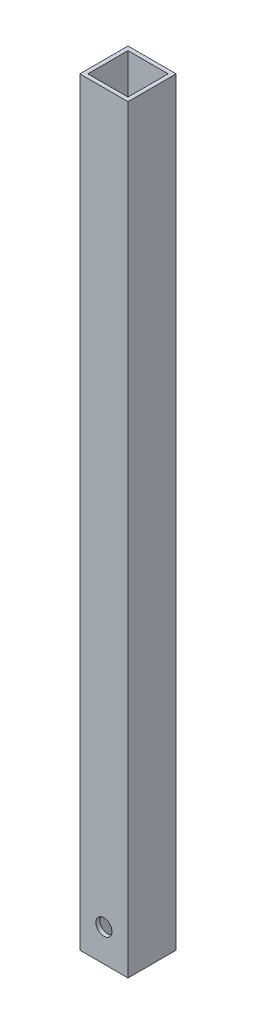
SolidWorks part; units mm, degrees
ref_plane "Front Plane" through (0, 0, 0) normal (0, 0, 1) x (1, 0, 0)
ref_plane "Top Plane" through (0, 0, 0) normal (0, 1, 0) x (1, 0, 0)
ref_plane "Right Plane" through (0, 0, 0) normal (1, 0, 0) x (0, 0, -1)
sketch "Sketch1" plane through (0, 0, 0) normal (0, 1, 0) x (1, 0, 0)
  line L1 (-7.9375, -7.9375) -> (7.9375, -7.9375)
  line L2 (-7.9375, -7.9375) -> (-7.9375, 7.9375)
  line L3 (-7.9375, 7.9375) -> (7.9375, 7.9375)
  line L4 (7.9375, -7.9375) -> (7.9375, 7.9375)
  line L5 (-7.9375, -7.9375) -> (7.9375, 7.9375) construction
  line L6 (-7.9375, 7.9375) -> (7.9375, -7.9375) construction
  line L7 (-9.525, -9.525) -> (9.525, -9.525)
  line L8 (-9.525, -9.525) -> (-9.525, 9.525)
  line L9 (-9.525, 9.525) -> (9.525, 9.525)
  line L10 (9.525, -9.525) -> (9.525, 9.525)
  line L11 (-9.525, -9.525) -> (9.525, 9.525) construction
  line L12 (-9.525, 9.525) -> (9.525, -9.525) construction
  point P0 (0, 0)
  point P6 (0, 0)
  dimension "D1" = 19.05
  dimension "D2" = 1.5875
extrude "Boss-Extrude1" add sketch "Sketch1" along normal blind 300
sketch "Sketch2" plane through (0, 0, 9.525) normal (0, 0, 1) x (1, 0, 0)
  circle A0 centre (0, 12.7) radius 3.175
  dimension "D1" = 6.35
  dimension "D2" = 12.7
extrude "Cut-Extrude1" cut sketch "Sketch2" against normal through all
